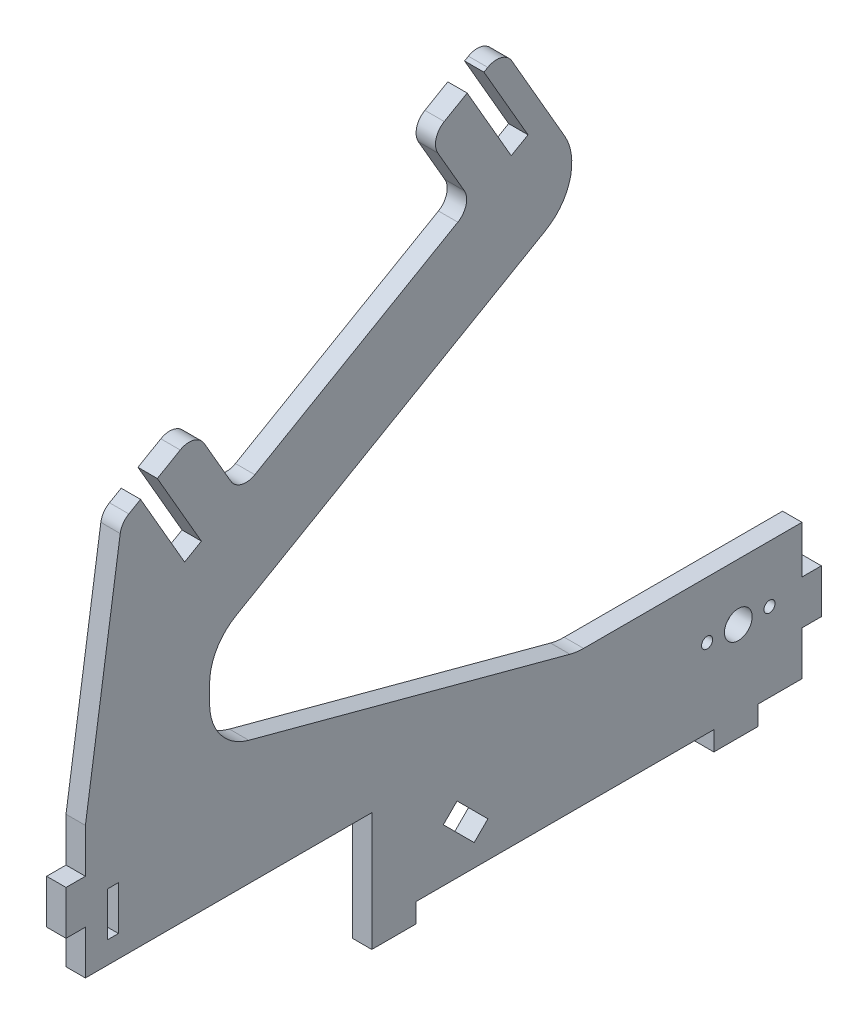
SolidWorks part; units mm, degrees
ref_plane "Front Plane" through (0, 0, 0) normal (0, 0, 1) x (1, 0, 0)
ref_plane "Top Plane" through (0, 0, 0) normal (0, 1, 0) x (1, 0, 0)
ref_plane "Right Plane" through (0, 0, 0) normal (1, 0, 0) x (0, 0, -1)
sketch "Sketch1" plane through (5.715, 0, 0) normal (-1, 0, 0) x (0, 0, 1)
  line L0 (-20.6462, 31.7964) -> (-20.6462, 38.1464)
  line L1 (41.3538, 29.0024) -> (35.0038, 29.0024)
  line L2 (41.3538, 29.0024) -> (41.3538, 46.0839)
  line L3 (41.3538, 46.0839) -> (82.6288, 46.0839)
  line L4 (72.2611, 103.2469) -> (74.6808, 101.8499) construction
  line L5 (73.4108, 99.6502) -> (74.6808, 101.8499) construction
  line L6 (82.6288, 52.4339) -> (82.6288, 46.0839)
  line L7 (77.4304, 100.2624) -> (66.7618, 106.4219)
  line L8 (35.0038, 29.0024) -> (35.0038, 31.7964)
  line L9 (35.0038, 31.7964) -> (-7.9462, 31.7964)
  line L10 (-7.9462, 31.7964) -> (-7.9462, 29.0024)
  line L11 (-7.9462, 29.0024) -> (-14.2962, 29.0024)
  line L12 (-14.2962, 29.0024) -> (-14.2962, 31.7964)
  line L13 (-14.2962, 31.7964) -> (-20.6462, 31.7964)
  line L14 (82.6288, 52.4339) -> (85.4228, 52.4339)
  line L15 (85.4228, 52.4339) -> (85.4228, 58.7839)
  line L16 (85.4228, 58.7839) -> (82.6288, 58.7839)
  line L17 (82.6288, 58.7839) -> (82.6288, 65.1339)
  line L18 (-20.6462, 38.1464) -> (-23.4402, 38.1464)
  line L19 (72.9793, 73.5028) -> (61.9808, 79.8528) construction
  line L20 (-23.4402, 38.1464) -> (-23.4402, 44.4964)
  line L21 (-23.4402, 44.4964) -> (-20.6462, 44.4964)
  line L22 (-20.6462, 44.4964) -> (-20.6462, 51.3214)
  line L23 (-20.6462, 51.3214) -> (11.8314, 51.3214)
  line L24 (11.8314, 51.3214) -> (64.7304, 65.4956)
  line L25 (64.7304, 65.4956) -> (64.7304, 78.2653)
  line L26 (64.7304, 78.2653) -> (9.7378, 110.0153)
  line L27 (9.7378, 110.0153) -> (22.4378, 132.0124)
  line L28 (82.6288, 65.1339) -> (77.4304, 100.2624)
  line L29 (61.9808, 79.8528) -> (68.3308, 90.8514) construction
  line L31 (23.9174, 128.2252) -> (20.1074, 121.6261) construction
  line L33 (32.6288, 31.7964) -> (82.6288, 31.7964) construction
  line L36 (33.1063, 125.8529) -> (26.7563, 114.8544)
  line L37 (-5.9712, 48.1464) -> (-16.9712, 48.1464) construction
  line L38 (-17.4712, 47.6464) -> (-17.4712, 38.6464) construction
  line L39 (26.7563, 114.8544) -> (60.4118, 95.4234)
  line L40 (60.4118, 95.4234) -> (66.7618, 106.4219)
  line L41 (33.1063, 125.8529) -> (22.4378, 132.0124)
  line L42 (26.3371, 126.8282) -> (22.5271, 120.2291) construction
  line L43 (70.9911, 101.0472) -> (67.1811, 94.4481) construction
  line L44 (82.6288, 57.1964) -> (82.6288, 31.7964) construction
  line L45 (44.5288, 44.4964) -> (44.5288, 31.7964) construction
  line L46 (88.9788, 44.4964) -> (44.5288, 44.4964) construction
  dimension "D1" = 6.35
  dimension "D2" = 0
  dimension "D3" = 3.175
  dimension "D4" = 2.794
  dimension "D5" = 6.35
  dimension "D6" = 6.35
  dimension "D7" = 6.35
  dimension "D8" = 2.794
  dimension "D9" = 3.175
  dimension "D10" = 3.175
  dimension "D11" = 6.35
  dimension "D12" = 6.35
  dimension "D13" = 6.35
  dimension "D14" = 2.794
  dimension "D15" = 6.35
  dimension "D16" = 3.175
  dimension "D17" = 3.175
  dimension "D18" = 45
  dimension "D19" = 12.7
  dimension "D20" = 12.7
  dimension "D21" = 6.35
  dimension "D22" = 6.35
  dimension "D23" = 3.175
  dimension "D24" = 1.5875
extrude "Boss-Extrude1" add sketch "Sketch1" along normal blind 2.794
sketch "Sketch2" plane through (2.921, 0, 0) normal (-1, 0, 0) x (0, 0, 1)
  line L1 (79.4538, 55.6089) -> (77.8663, 55.6089)
  line L2 (79.4538, 55.6089) -> (79.4538, 49.2589)
  line L3 (79.4538, 49.2589) -> (77.8663, 49.2589)
  line L4 (77.8663, 55.6089) -> (77.8663, 49.2589)
  line L6 (82.6288, 58.7839) -> (82.6288, 65.1339) construction
  line L7 (85.4228, 58.7839) -> (82.6288, 58.7839) construction
  dimension "D1" = 1.5875
  dimension "D2" = 3.175
  dimension "D3" = 6.35
  dimension "D4" = 3.175
extrude "Cut-Extrude1" cut sketch "Sketch2" against normal through all
fillet "Fillet2" radius 2.54 6 edges at (4.318, 95.4234, 60.4118) (4.318, 114.8544, 26.7563) (4.318, 100.2624, 77.4304) (4.318, 106.4219, 66.7618) (4.318, 125.8529, 33.1063) (4.318, 132.0124, 22.4378)
fillet "Fillet3" radius 7.62 4 edges at (4.318, 51.3214, 11.8314) (4.318, 78.2653, 64.7304) (4.318, 65.4956, 64.7304) (4.318, 110.0153, 9.7378)
sketch "Sketch4" plane through (2.921, 0, 0) normal (-1, 0, 0) x (0, 0, 1)
  circle A0 centre (-11.4712, 43.1464) radius 2
  circle A1 centre (-6.9712, 43.1464) radius 0.8
  circle A2 centre (-15.9712, 43.1464) radius 0.8
  dimension "D1" = 1.6
  dimension "D2" = 1.6
  dimension "D3" = 4
extrude "Cut-Extrude2" cut sketch "Sketch4" against normal through all
sketch "Sketch5" plane through (2.921, 0, 0) normal (-1, 0, 0) x (0, 0, 1)
  line L4 (29.0657, 41.392) -> (24.6195, 36.9458)
  line L5 (24.6195, 36.9458) -> (26.5951, 34.9702)
  line L6 (26.5951, 34.9702) -> (31.0413, 39.4164)
  line L7 (31.0413, 39.4164) -> (29.0657, 41.392)
  line L8 (29.0657, 41.392) -> (24.6195, 36.9458)
  line L9 (24.6195, 36.9458) -> (26.5951, 34.9702)
  line L10 (26.5951, 34.9702) -> (31.0413, 39.4164)
  line L11 (31.0413, 39.4164) -> (29.0657, 41.392)
  dimension "D1" = 0
extrude "Cut-Extrude3" cut sketch "Sketch5" against normal through all
sketch "Sketch7" plane through (2.921, 0, 0) normal (-1, 0, 0) x (0, 0, 1)
  line L0 (27.6071, 129.0279) -> (21.2571, 118.0294)
  line L1 (27.6071, 129.0279) -> (25.1874, 130.4249)
  line L2 (21.2571, 118.0294) -> (18.8374, 119.4264)
  line L3 (25.1874, 130.4249) -> (18.8374, 119.4264)
  line L4 (30.9066, 127.1229) -> (24.6375, 130.7424) construction
  line L5 (26.3371, 126.8282) -> (22.5271, 120.2291) construction
  line L6 (23.9174, 128.2252) -> (20.1074, 121.6261) construction
  line L7 (74.6808, 101.8499) -> (68.3308, 90.8514)
  line L8 (74.6808, 101.8499) -> (72.2611, 103.2469)
  line L9 (68.3308, 90.8514) -> (65.9111, 92.2484)
  line L10 (72.2611, 103.2469) -> (65.9111, 92.2484)
  line L11 (76.3674, 100.8761) -> (68.9615, 105.1519) construction
  line L12 (73.4108, 99.6502) -> (69.6008, 93.0511) construction
  line L13 (70.9911, 101.0472) -> (67.1811, 94.4481) construction
  dimension "D1" = 12.7
  dimension "D2" = 12.7
extrude "Cut-Extrude4" cut sketch "Sketch7" against normal through all
equation "\"D1@Boss-Extrude1\"=\"thick@assy.sldasm\""
equation "\"D4@Sketch1\"=\"thick@assy.sldasm\""
equation "\"D8@Sketch1\"=\"thick@assy.sldasm\""
equation "\"D14@Sketch1\"=\"thick@assy.sldasm\""
